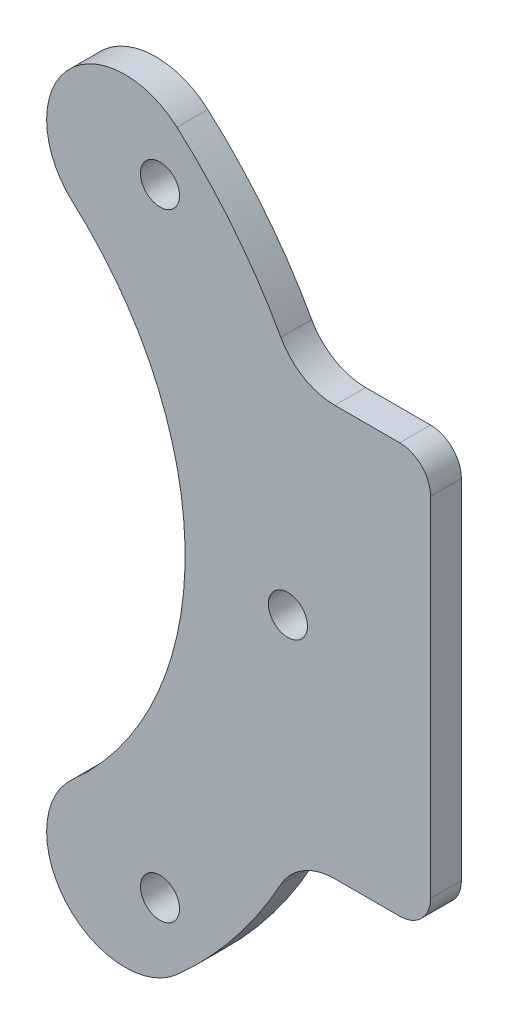
SolidWorks part; units mm, degrees
ref_plane "前视基准面" through (0, 0, 0) normal (0, 0, 1) x (1, 0, 0)
ref_plane "上视基准面" through (0, 0, 0) normal (0, 1, 0) x (1, 0, 0)
ref_plane "右视基准面" through (0, 0, 0) normal (1, 0, 0) x (0, 0, -1)
other "Configuration Table"
sketch "草图1" plane through (0, 0, 0) normal (0, 0, 1) x (1, 0, 0)
  circle A0 centre (0, 0) radius 42.5 construction
  circle A1 centre (0, 0) radius 47.75
  circle A2 centre (0, 0) radius 32.5
  circle A3 centre (0, 42.5) radius 1.9
  circle A4 centre (30.052, 30.052) radius 1.9
  circle A5 centre (42.5, 0) radius 1.9
  circle A6 centre (30.052, -30.052) radius 1.9
  circle A7 centre (0, -42.5) radius 1.9
  circle A8 centre (-30.052, -30.052) radius 1.9
  circle A9 centre (-42.5, 0) radius 1.9
  circle A10 centre (-30.052, 30.052) radius 1.9
  point P24 (0, 0)
  dimension "D1" = 85
  dimension "D2" = 95.5
  dimension "D3" = 65
  dimension "D4" = 3.8
  dimension "D6" = 45
  dimension "D5" = 8
extrude "凸台-拉伸1" add sketch "草图1" along normal blind 3
sketch "草图2" plane through (0, 0, 0) normal (0, 0, -1) x (-1, 0, 0)
  line L0 (-47.75, 0) -> (47.75, 0) construction
  circle A0 centre (-26.6461, 30) radius 7.625
  circle A1 centre (-26.6461, -30) radius 7.625
  circle A2 centre (0, 0) radius 47.75 construction
  circle A3 centre (0, 0) radius 32.5 construction
  circle A5 centre (0, 0) radius 47.75
  circle A6 centre (0, 0) radius 47.75
  circle M5 centre (0, 0) radius 47.75
  circle M6 centre (0, 0) radius 32.5
  circle M7 centre (0, 42.5) radius 1.9
  circle M11 centre (0, -42.5) radius 1.9
  circle M12 centre (30.052, -30.052) radius 1.9
  circle M13 centre (42.5, 0) radius 1.9
  circle M14 centre (30.052, 30.052) radius 1.9
  dimension "D1" = 0
  dimension "D2" = 60
extrude "切除-拉伸1" cut sketch "草图2" against normal blind 3 contours L0 A6 A0 M6 M13 M7 M14 | L0 A1 M6 M5 M13 M12 M11
sketch "草图3" plane through (0, 0, 0) normal (0, 0, -1) x (-1, 0, 0)
  line L0 (-56.3827, 19.95) -> (-56.3827, -19.95)
  line L1 (0, 0) -> (-56.3827, 0) construction
  line L2 (-56.3827, 19.95) -> (-43.3827, 19.95)
  line L3 (-56.3827, -19.95) -> (-43.3827, -19.95)
  arc A4 (-21.5825, 24.2991) -> (-31.7097, 35.7009) centre (-26.6461, 30) ccw
  arc A5 (-31.7097, 35.7009) -> (-31.7097, -35.7009) centre (0, 0) ccw
  arc A6 (-31.7097, -35.7009) -> (-21.5825, -24.2991) centre (-26.6461, -30) ccw
  arc A7 (-21.5825, 24.2991) -> (-21.5825, -24.2991) centre (0, 0) ccw
  arc A8 (-21.5825, 24.2991) -> (-31.7097, 35.7009) centre (-26.6461, 30) ccw
  arc A9 (-31.7097, 35.7009) -> (-31.7097, -35.7009) centre (0, 0) ccw
  arc A10 (-31.7097, -35.7009) -> (-21.5825, -24.2991) centre (-26.6461, -30) ccw
  arc A11 (-21.5825, 24.2991) -> (-21.5825, -24.2991) centre (0, 0) ccw
  arc M12 (-31.7097, 35.7009) -> (-31.7097, -35.7009) centre (0, 0) ccw
  dimension "D2" = 39.9
  dimension "D3" = 13
  dimension "D1" = 0
extrude "凸台-拉伸2" add sketch "草图3" against normal blind 3 contours L1 L2 L0 M12 | A9 L1 L0 L3
fillet "圆角1" radius 3 2 edges at (56.3827, -19.95, 1.5) (56.3827, 19.95, 1.5)
fillet "圆角2" radius 6 2 edges at (43.3827, -19.95, 1.5) (43.3827, 19.95, 1.5)
